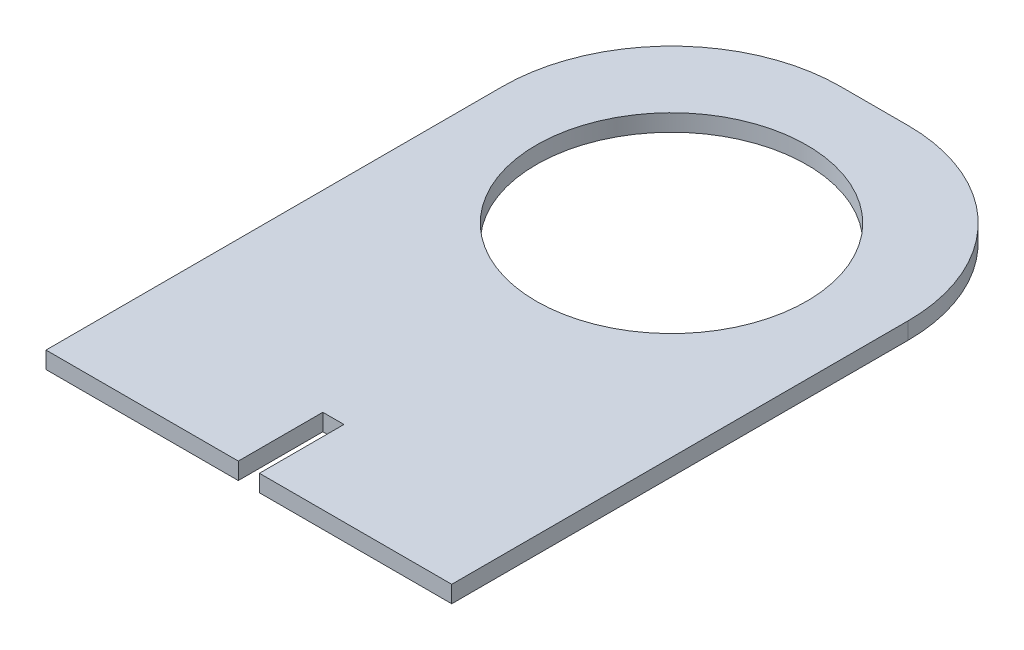
SolidWorks part; units mm, degrees
ref_plane "Front Plane" through (0, 0, 0) normal (0, 0, 1) x (1, 0, 0)
ref_plane "Top Plane" through (0, 0, 0) normal (0, 1, 0) x (1, 0, 0)
ref_plane "Right Plane" through (0, 0, 0) normal (1, 0, 0) x (0, 0, -1)
sketch "Sketch1" plane through (0, 0, 0) normal (0, 1, 0) x (1, 0, 0)
  line L0 (0, 0) -> (0, -63.5) construction
  line L1 (-30.48, -30.48) -> (30.48, -30.48)
  line L2 (-30.48, -30.48) -> (-30.48, 30.48)
  line L3 (-30.48, 30.48) -> (30.48, 30.48)
  line L4 (30.48, -30.48) -> (30.48, 30.48)
  line L5 (-30.48, -30.48) -> (30.48, 30.48) construction
  line L6 (-30.48, 30.48) -> (30.48, -30.48) construction
  line L7 (0, -63.5) -> (-30.48, -63.5)
  line L8 (-30.48, -63.5) -> (-30.48, -30.48)
  line L9 (0, -63.5) -> (30.48, -63.5)
  line L10 (30.48, -63.5) -> (30.48, -30.48)
  line L11 (0, -63.5) -> (0, -50.8)
  line L12 (1.5875, -50.8) -> (-1.5875, -50.8)
  line L13 (-1.5875, -50.8) -> (-1.5875, -63.5)
  line L14 (1.5875, -50.8) -> (1.5875, -63.5)
  circle A0 centre (0, 0) radius 20.32
  point P14 (0, -50.8)
  dimension "D1" = 40.64
  dimension "D2" = 60.96
  dimension "D3" = 63.5
  dimension "D4" = 12.7
  dimension "D5" = 3.175
extrude "Boss-Extrude1" add sketch "Sketch1" along normal blind 2.54 contours L9 L10 L1 L8 L7 | L1 L4 L3 L2 A0
fillet "Fillet1" radius 25.4 2 edges at (-30.48, 1.27, -30.48) (30.48, 1.27, -30.48)
